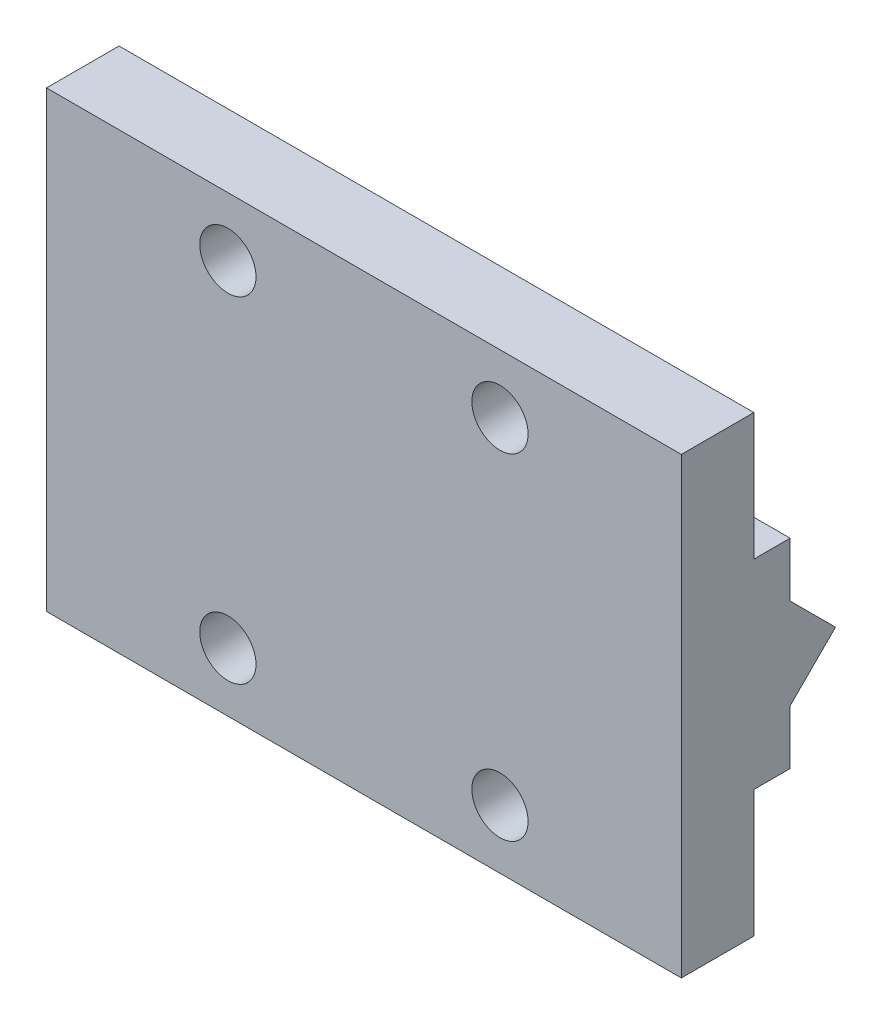
SolidWorks part; units mm, degrees
ref_plane "Front Plane" through (0, 0, 0) normal (0, 0, 1) x (1, 0, 0)
ref_plane "Top Plane" through (0, 0, 0) normal (0, 1, 0) x (1, 0, 0)
ref_plane "Right Plane" through (0, 0, 0) normal (1, 0, 0) x (0, 0, -1)
sketch "Sketch1" plane through (0, 0, 0) normal (0, 0, 1) x (1, 0, 0)
  line L1 (-46.4809, 24.5601) -> (23.5191, 24.5601)
  line L2 (-46.4809, 24.5601) -> (-46.4809, -25.4399)
  line L3 (-46.4809, -25.4399) -> (23.5191, -25.4399)
  line L4 (23.5191, 24.5601) -> (23.5191, -25.4399)
  circle A0 centre (-26.4809, 18.0601) radius 3.1
  circle A1 centre (3.5191, 18.0601) radius 3.1
  circle A2 centre (-26.4809, -18.9399) radius 3.1
  circle A3 centre (3.5191, -18.9399) radius 3.1
  dimension "D11" = 6.2
  dimension "D12" = 6.2
  dimension "D13" = 6.2
  dimension "D14" = 6.2
  dimension "D1" = 50
  dimension "D2" = 70
  dimension "D3" = 6.5
  dimension "D4" = 6.5
  dimension "D5" = 20
  dimension "D6" = 20
  dimension "D7" = 6.5
  dimension "D8" = 20
  dimension "D9" = 6.5
  dimension "D10" = 20
extrude "Boss-Extrude1" add sketch "Sketch1" along normal blind 8
sketch "Sketch3" plane through (0, 0, 0) normal (0, 0, -1) x (-1, 0, 0)
  line L0 (-23.5191, 10.5601) -> (46.4809, 10.5601)
  line L1 (-23.5191, -25.4399) -> (-23.5191, 24.5601) construction
  line L2 (46.4809, 24.5601) -> (46.4809, -25.4399) construction
  line L3 (-23.5191, -11.4399) -> (46.4809, -11.4399)
  line L4 (-23.5191, 24.5601) -> (46.4809, 24.5601) construction
  line L5 (-23.5191, 10.5601) -> (-23.5191, -11.4399)
  line L6 (46.4809, 10.5601) -> (46.4809, -11.4399)
  dimension "D1" = 22
  dimension "D2" = 14
extrude "Boss-Extrude2" add sketch "Sketch3" along normal blind 4
sketch "Sketch4" plane through (-46.4809, 0, 0) normal (-1, 0, 0) x (0, 0, 1)
  line L0 (-4, -5.4399) -> (-9, -0.4399)
  line L1 (-4, -11.4399) -> (-4, 10.5601) construction
  line L2 (-9, -0.4399) -> (-4, 4.5601)
  line L3 (-4, -11.4399) -> (-4, -0.4399)
  line L4 (-4, -5.4399) -> (-4, 4.5601)
  line M6 (-4, 10.5601) -> (-4, -11.4399)
  dimension "D1" = 5
  dimension "D2" = 45
  dimension "D3" = 45
  dimension "D4" = 11
extrude "Boss-Extrude3" add sketch "Sketch4" against normal blind 70 contours L2 L0 M6
